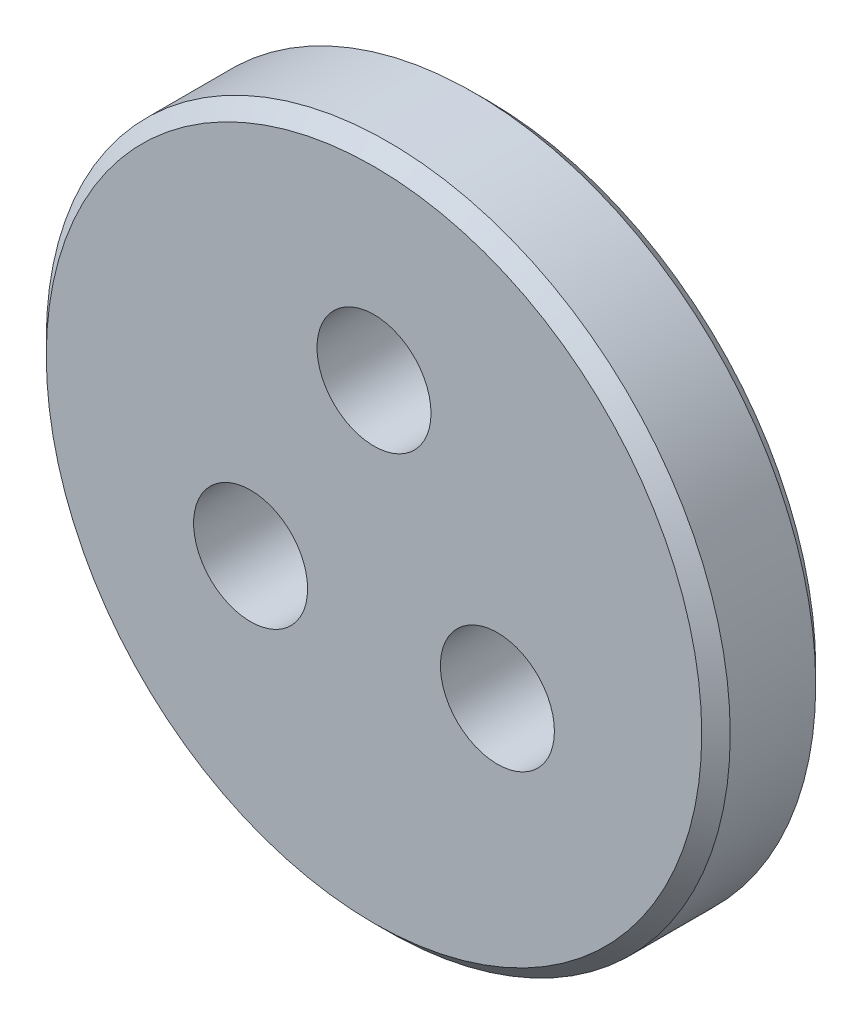
SolidWorks part; units mm, degrees
material "PEI"
ref_plane "前视基准面" through (0, 0, 0) normal (0, 0, 1) x (1, 0, 0)
ref_plane "上视基准面" through (0, 0, 0) normal (0, 1, 0) x (1, 0, 0)
ref_plane "右视基准面" through (0, 0, 0) normal (1, 0, 0) x (0, 0, -1)
other "Configuration Table"
sketch "草图1" plane through (0, 0, 0) normal (0, 0, 1) x (1, 0, 0)
  circle A0 centre (0, 0) radius 12
  circle A1 centre (0, 0) radius 5 construction
  circle A2 centre (0, 5) radius 2
  circle A3 centre (4.3301, -2.5) radius 2
  circle A4 centre (-4.3301, -2.5) radius 2
  dimension "D1" = 24
  dimension "D2" = 10
  dimension "D3" = 4
  dimension "D4" = 3
extrude "凸台-拉伸1" add sketch "草图1" along normal blind 4
chamfer "倒角1" distance 0.5 angle 45 2 edges at (12, 0, 0) (12, 0, 4)
